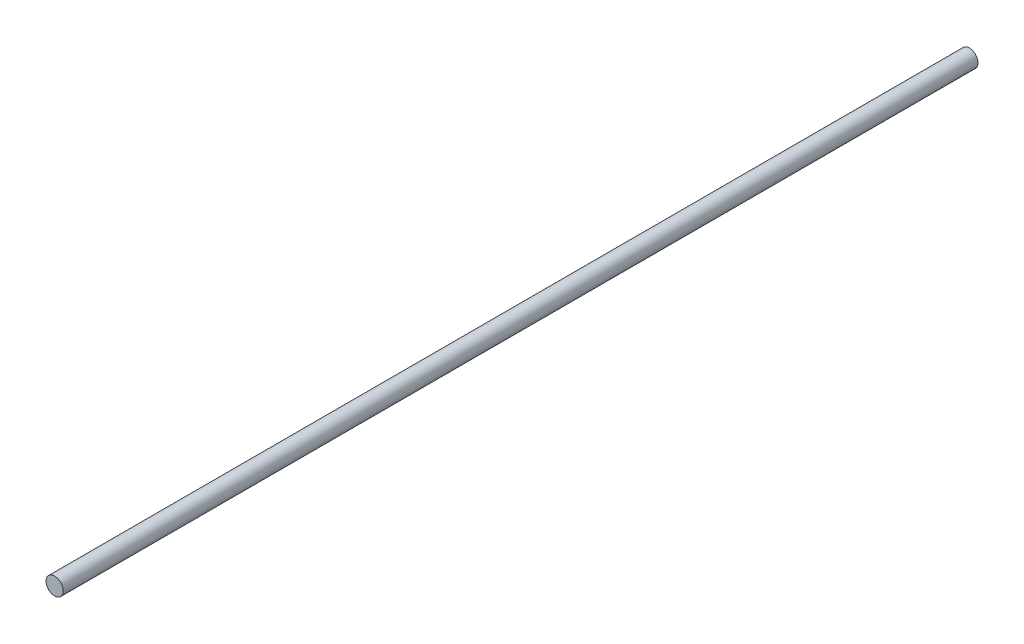
SolidWorks part; units mm, degrees
material "合金钢"
ref_plane "前视基准面" through (0, 0, 0) normal (0, 0, 1) x (1, 0, 0)
ref_plane "上视基准面" through (0, 0, 0) normal (0, 1, 0) x (1, 0, 0)
ref_plane "右视基准面" through (0, 0, 0) normal (1, 0, 0) x (0, 0, -1)
sketch "草图1" plane through (0, 0, 0) normal (0, 0, 1) x (1, 0, 0)
  circle A0 centre (0, 0) radius 4
  dimension "D1" = 8
extrude "凸台-拉伸1" add sketch "草图1" along normal blind 275 and the other way blind 150
